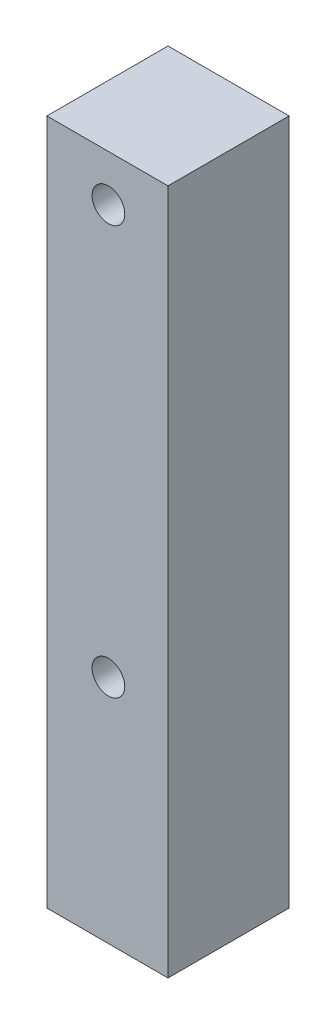
SolidWorks part; units mm, degrees
material "6061-T6 (SS)"
ref_plane "Front Plane" through (0, 0, 0) normal (0, 0, 1) x (1, 0, 0)
ref_plane "Top Plane" through (0, 0, 0) normal (0, 1, 0) x (1, 0, 0)
ref_plane "Right Plane" through (0, 0, 0) normal (1, 0, 0) x (0, 0, -1)
sketch "Sketch1" plane through (0, 0, 0) normal (0, 1, 0) x (1, 0, 0)
  line L1 (-3.9423, 4.4231) -> (6.0577, 4.4231)
  line L2 (-3.9423, 4.4231) -> (-3.9423, -5.5769)
  line L3 (-3.9423, -5.5769) -> (6.0577, -5.5769)
  line L4 (6.0577, 4.4231) -> (6.0577, -5.5769)
  dimension "D1" = 10
  dimension "D2" = 10
extrude "Boss-Extrude1" add sketch "Sketch1" along normal blind 56.642
sketch "Sketch2" plane through (0, 0, 0) normal (0, -1, 0) x (1, 0, 0)
  line L0 (6.0577, 5.5769) -> (6.0577, -4.4231) construction
  line L1 (-3.9423, 5.5769) -> (6.0577, 5.5769)
  line L2 (-3.9423, 5.5769) -> (-3.9423, 4.2815)
  line L3 (-3.9423, 4.2815) -> (6.0577, 4.2815)
  line L4 (6.0577, 5.5769) -> (6.0577, 4.2815)
  dimension "D1" = 1.2954
sketch "Sketch3" plane through (0, 0, 5.5769) normal (0, 0, 1) x (1, 0, 0)
  circle A0 centre (1.1377, 19.05) radius 1.35
  circle A1 centre (1.1377, 52.832) radius 1.35
  dimension "D1" = 2.7
  dimension "D2" = 2.7
extrude "Cut-Extrude1" cut sketch "Sketch3" against normal up to surface (10 mm away) up to face at (1.0577, 28.321, -4.4231)
sketch "Sketch4" plane through (-3.9423, 0, 0) normal (-1, 0, 0) x (0, 0, 1)
  circle A0 centre (0.5769, 12.6907) radius 1.35
  circle A1 centre (0.5769, 46.642) radius 1.35
  dimension "D1" = 2.7
  dimension "D2" = 2.7
extrude "Cut-Extrude2" cut sketch "Sketch4" against normal blind 7
sketch "Sketch8" plane through (0, 0, 0) normal (0, -1, 0) x (-1, 0, 0)
  circle A0 centre (-0.9777, -0.4969) radius 1.48
extrude "Cut-Extrude3" cut sketch "Sketch8" against normal blind 6
